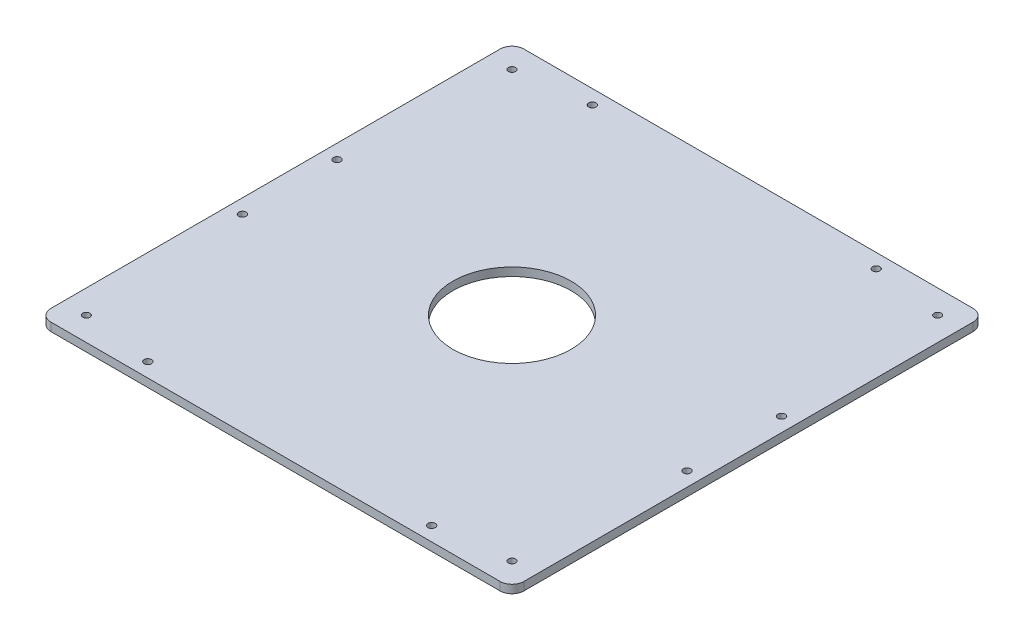
SolidWorks part; units mm, degrees
ref_plane "前视基准面" through (0, 0, 0) normal (0, 0, 1) x (1, 0, 0)
ref_plane "上视基准面" through (0, 0, 0) normal (0, 1, 0) x (1, 0, 0)
ref_plane "右视基准面" through (0, 0, 0) normal (1, 0, 0) x (0, 0, -1)
sketch "草图1" plane through (0, 0, 0) normal (0, 1, 0) x (1, 0, 0)
  line L0 (0, 100) -> (0, -100) construction
  line L1 (-100, 100) -> (100, 100)
  line L2 (-100, 100) -> (-100, -32.6875)
  line L3 (-100, -100) -> (100, -100)
  line L4 (100, 100) -> (100, -32.6875)
  line L11 (-100, -80.6875) -> (-100, -100)
  line L12 (100, -80.6875) -> (100, -100)
  line L13 (-100, 0) -> (100, 0) construction
  line L14 (100, -32.6875) -> (100, -80.6875)
  line L15 (-100, -32.6875) -> (-100, -80.6875)
  circle A17 centre (60, 94) radius 1.55
  circle A18 centre (60, -94) radius 1.55
  circle A19 centre (94, 20) radius 1.55
  circle A20 centre (94, -20) radius 1.55
  circle A21 centre (-60, -94) radius 1.55
  circle A22 centre (-94, -20) radius 1.55
  circle A23 centre (-94, 20) radius 1.55
  circle A24 centre (-60, 94) radius 1.55
  circle A40 centre (0, 0) radius 25
  circle A41 centre (-90, -90) radius 1.5
  circle A42 centre (-90, 90) radius 1.5
  circle A43 centre (90, 90) radius 1.5
  circle A44 centre (90, -90) radius 1.5
  point P66 (0, 0)
  dimension "D5" = 50
  dimension "D6" = 10
  dimension "D30" = 3.1
  dimension "D32" = 3.1
  dimension "D35" = 3.1
  dimension "D7" = 10
  dimension "D8" = 3
  dimension "D1" = 200
  dimension "D2" = 200
  dimension "D3" = 100
  dimension "D4" = 100
  dimension "D29" = 6
  dimension "D31" = 60
  dimension "D33" = 6
  dimension "D34" = 60
  dimension "D36" = 6
  dimension "D37" = 20
extrude "凸台-拉伸1" add sketch "草图1" along normal blind 3.5
fillet "圆角1" radius 5 4 edges at (100, 1.75, -100) (-100, 1.75, -100) (-100, 1.75, 100) (100, 1.75, 100)
